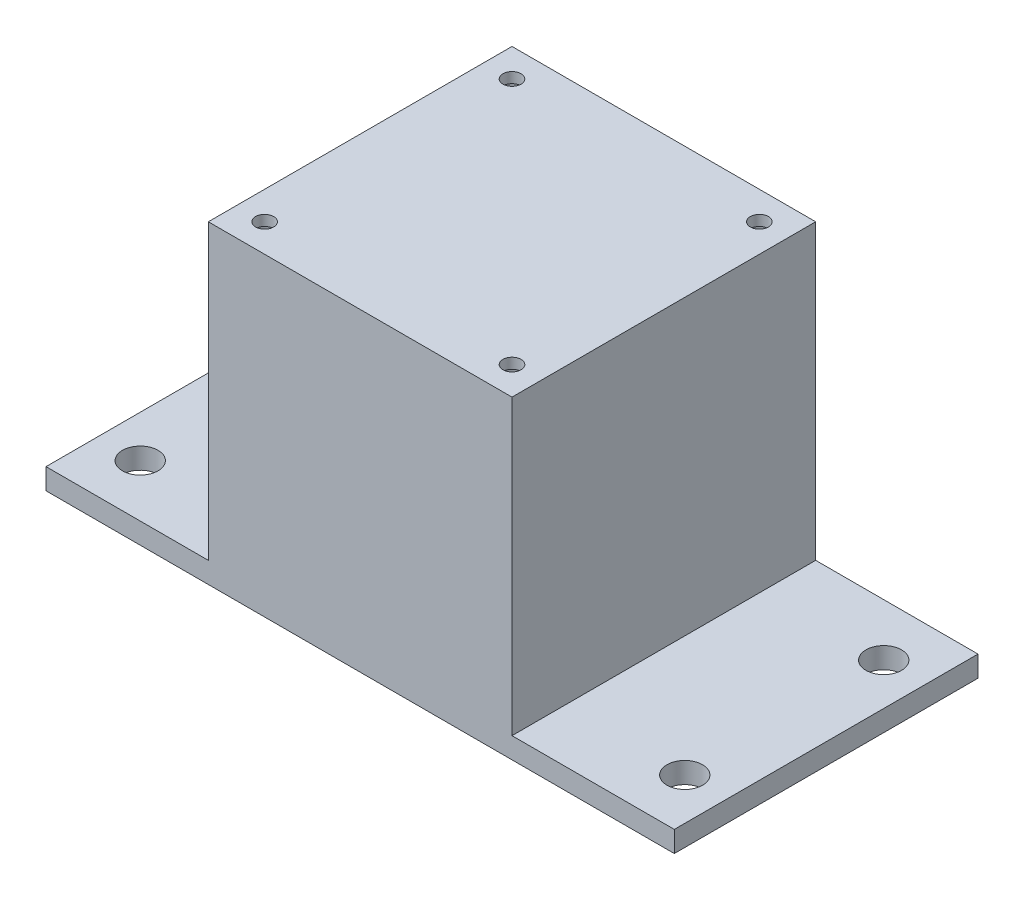
SolidWorks part; units mm, degrees
ref_plane "Front Plane" through (0, 0, 0) normal (0, 0, 1) x (1, 0, 0)
ref_plane "Top Plane" through (0, 0, 0) normal (0, 1, 0) x (1, 0, 0)
ref_plane "Right Plane" through (0, 0, 0) normal (1, 0, 0) x (0, 0, -1)
sketch "Sketch1" plane through (0, 0, 0) normal (0, 1, 0) x (1, 0, 0)
  line L0 (-1.4225, 15.1389) -> (-1.4225, -32.1148) construction
  line L1 (-39.5225, 15.1389) -> (36.6775, 15.1389)
  line L2 (-39.5225, 15.1389) -> (-39.5225, -21.6911)
  line L3 (-39.5225, -21.6911) -> (36.6775, -21.6911)
  line L4 (36.6775, 15.1389) -> (36.6775, -21.6911)
  line L5 (36.6775, -3.2761) -> (-38.4515, -3.2761) construction
  circle A0 centre (-16.4225, 11.7239) radius 1.1
  circle A1 centre (13.5775, 11.7239) radius 1.1
  circle A2 centre (13.5775, -18.2761) radius 1.1
  circle A3 centre (-16.4225, -18.2761) radius 1.1
  circle A4 centre (31.5975, -15.3411) radius 2.159
  circle A5 centre (31.5975, 8.7889) radius 2.159
  circle A6 centre (-34.4425, -15.3411) radius 2.159
  circle A7 centre (-34.4425, 8.7889) radius 2.159
  dimension "D3" = 2.2
  dimension "D4" = 30
  dimension "D6" = 4.318
  dimension "D1" = 76.2
  dimension "D2" = 36.83
  dimension "D5" = 30
  dimension "D7" = 33.02
  dimension "D8" = 24.13
extrude "Boss-Extrude1" add sketch "Sketch1" along normal blind 38.1
sketch "Sketch3" plane through (0, 0, 0) normal (0, -1, 0) x (1, 0, 0)
  line L0 (-1.4225, 21.6911) -> (-1.4225, -15.1389) construction
  line L1 (-39.5225, 21.6911) -> (36.6775, 21.6911) construction
  line L2 (36.6775, -15.1389) -> (-39.5225, -15.1389) construction
  line L3 (36.6775, 3.2761) -> (-39.5225, 3.2761) construction
  line L4 (36.6775, 21.6911) -> (36.6775, -15.1389) construction
  line L5 (-39.5225, -15.1389) -> (-39.5225, 21.6911) construction
  circle A0 centre (-16.4225, 18.2761) radius 2.54
  circle A1 centre (-16.4225, 18.2761) radius 1.1 construction
  circle A2 centre (13.5775, 18.2761) radius 2.54
  circle A3 centre (13.5775, -11.7239) radius 2.54
  circle A4 centre (-16.4225, -11.7239) radius 2.54
  dimension "D1" = 5.08
extrude "Cut-Extrude2" cut sketch "Sketch3" against normal blind 36.83
sketch "Sketch4" plane through (0, 38.1, 0) normal (0, 1, 0) x (1, 0, 0)
  line L0 (-39.5225, -21.6911) -> (36.6775, -21.6911) construction
  line L1 (-39.5225, 15.1389) -> (-19.8375, 15.1389)
  line L2 (-39.5225, 15.1389) -> (-39.5225, -21.6911)
  line L3 (-39.5225, -21.6911) -> (-19.8375, -21.6911)
  line L4 (-19.8375, 15.1389) -> (-19.8375, -21.6911)
  line L6 (36.6775, 15.1389) -> (16.9925, 15.1389)
  line L7 (36.6775, 15.1389) -> (36.6775, -21.6911)
  line L8 (36.6775, -21.6911) -> (16.9925, -21.6911)
  line L9 (16.9925, 15.1389) -> (16.9925, -21.6911)
  dimension "D1" = 36.83
extrude "Cut-Extrude3" cut sketch "Sketch4" against normal blind 35.56
sketch "Sketch5" plane through (0, 0, 0) normal (0, -1, 0) x (1, 0, 0)
  line L0 (9.7675, 14.4661) -> (13.5775, 14.4661)
  line L1 (-12.6125, 18.2761) -> (9.7675, 18.2761)
  line L2 (-12.6125, 18.2761) -> (-12.6125, 14.4661)
  line L3 (-12.6125, -11.7239) -> (9.7675, -11.7239)
  line L4 (9.7675, 18.2761) -> (9.7675, 14.4661)
  line L5 (-16.4225, 14.4661) -> (-12.6125, 14.4661)
  line L6 (-16.4225, 14.4661) -> (-16.4225, -7.9139)
  line L7 (-16.4225, -7.9139) -> (-12.6125, -7.9139)
  line L8 (13.5775, 14.4661) -> (13.5775, -7.9139)
  line L9 (-12.6125, -7.9139) -> (-12.6125, -11.7239)
  line L10 (9.7675, -7.9139) -> (13.5775, -7.9139)
  line L11 (9.7675, -7.9139) -> (9.7675, -11.7239)
  circle A1 centre (13.5775, -11.7239) radius 2.54 construction
  circle A2 centre (-16.4225, -11.7239) radius 2.54 construction
  circle A3 centre (13.5775, 18.2761) radius 2.54 construction
  circle A4 centre (-16.4225, 18.2761) radius 2.54 construction
  circle A5 centre (13.5775, -11.7239) radius 2.54
  circle A6 centre (-16.4225, -11.7239) radius 2.54
  circle A7 centre (13.5775, 18.2761) radius 2.54
  circle A8 centre (-16.4225, 18.2761) radius 2.54
  dimension "D1" = 3.81
  dimension "D2" = 3.81
  dimension "D3" = 3.81
  dimension "D4" = 3.81
extrude "Cut-Extrude4" cut sketch "Sketch5" against normal blind 35.56 contours L11 L10 L8 L0 L4 L1 L2 L5 L6 L7 L9 L3
